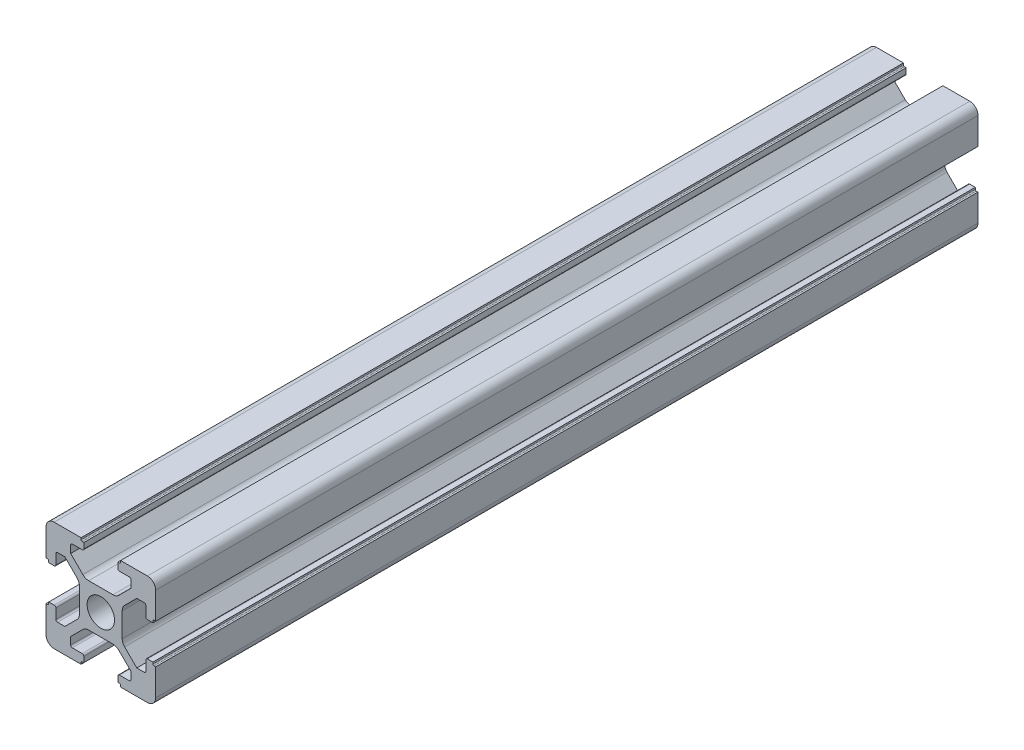
SolidWorks part; units mm, degrees
ref_plane "前视基准面" through (0, 0, 0) normal (0, 0, 1) x (1, 0, 0)
ref_plane "上视基准面" through (0, 0, 0) normal (0, 1, 0) x (1, 0, 0)
ref_plane "右视基准面" through (0, 0, 0) normal (1, 0, 0) x (0, 0, -1)
sketch "草图1" plane through (0, 0, 0) normal (0, 0, 1) x (1, 0, 0)
  line L0 (4.216, 3.2442) -> (6.4367, 5.4649)
  line L1 (6.4367, 5.4649) -> (7.7767, 5.4649)
  line L2 (8.0767, 5.1649) -> (8.0767, 3.3649)
  line L3 (8.3767, 3.0649) -> (9.3767, 3.0649)
  line L4 (9.3767, 3.0649) -> (9.3767, 3.3649)
  line L5 (9.5767, 3.5649) -> (9.8767, 3.5649)
  line L6 (9.8767, 3.5649) -> (9.8767, 8.4649)
  line L7 (8.3767, 9.9649) -> (3.4767, 9.9649)
  line L8 (3.4767, 9.9649) -> (3.4767, 9.6649)
  line L9 (3.2767, 9.4649) -> (2.9767, 9.4649)
  line L10 (2.9767, 9.4649) -> (2.9767, 8.4649)
  line L11 (3.2767, 8.1649) -> (5.0767, 8.1649)
  line L12 (5.3767, 7.8649) -> (5.3767, 6.5249)
  line L13 (5.3767, 6.5249) -> (3.156, 4.3042)
  line L14 (2.0953, 3.8649) -> (-2.342, 3.8649)
  line L15 (-3.4027, 4.3042) -> (-5.6233, 6.5249)
  line L16 (-5.6233, 6.5249) -> (-5.6233, 7.8649)
  line L17 (-5.3233, 8.1649) -> (-3.5233, 8.1649)
  line L18 (-3.2233, 8.4649) -> (-3.2233, 9.4649)
  line L19 (-3.2233, 9.4649) -> (-3.5233, 9.4649)
  line L20 (-3.7233, 9.6649) -> (-3.7233, 9.9649)
  line L21 (-3.7233, 9.9649) -> (-8.6233, 9.9649)
  line L22 (-10.1233, 8.4649) -> (-10.1233, 3.5649)
  line L23 (-10.1233, 3.5649) -> (-9.8233, 3.5649)
  line L24 (-9.6233, 3.3649) -> (-9.6233, 3.0649)
  line L25 (-9.6233, 3.0649) -> (-8.6233, 3.0649)
  line L26 (-8.3233, 3.3649) -> (-8.3233, 5.1649)
  line L27 (-8.0233, 5.4649) -> (-6.6833, 5.4649)
  line L28 (-6.6833, 5.4649) -> (-4.4627, 3.2442)
  line L29 (-4.0233, 2.1836) -> (-4.0233, -2.2538)
  line L30 (-4.4627, -3.3144) -> (-6.6833, -5.5351)
  line L31 (-6.6833, -5.5351) -> (-8.0233, -5.5351)
  line L32 (-8.3233, -5.2351) -> (-8.3233, -3.4351)
  line L33 (-8.6233, -3.1351) -> (-9.6233, -3.1351)
  line L34 (-9.6233, -3.1351) -> (-9.6233, -3.4351)
  line L35 (-9.8233, -3.6351) -> (-10.1233, -3.6351)
  line L36 (-10.1233, -3.6351) -> (-10.1233, -8.5351)
  line L37 (-8.6233, -10.0351) -> (-3.7233, -10.0351)
  line L38 (-3.7233, -10.0351) -> (-3.7233, -9.7351)
  line L39 (-3.5233, -9.5351) -> (-3.2233, -9.5351)
  line L40 (-3.2233, -9.5351) -> (-3.2233, -8.5351)
  line L41 (-3.5233, -8.2351) -> (-5.3233, -8.2351)
  line L42 (-5.6233, -7.9351) -> (-5.6233, -6.5951)
  line L43 (-5.6233, -6.5951) -> (-3.4027, -4.3744)
  line L44 (-2.342, -3.9351) -> (2.0953, -3.9351)
  line L45 (3.156, -4.3744) -> (5.3767, -6.5951)
  line L46 (5.3767, -6.5951) -> (5.3767, -7.9351)
  line L47 (5.0767, -8.2351) -> (3.2767, -8.2351)
  line L48 (2.9767, -8.5351) -> (2.9767, -9.5351)
  line L49 (2.9767, -9.5351) -> (3.2767, -9.5351)
  line L50 (3.4767, -9.7351) -> (3.4767, -10.0351)
  line L51 (3.4767, -10.0351) -> (8.3767, -10.0351)
  line L52 (9.8767, -8.5351) -> (9.8767, -3.6351)
  line L53 (9.8767, -3.6351) -> (9.5767, -3.6351)
  line L54 (9.3767, -3.4351) -> (9.3767, -3.1351)
  line L55 (9.3767, -3.1351) -> (8.3767, -3.1351)
  line L56 (8.0767, -3.4351) -> (8.0767, -5.2351)
  line L57 (7.7767, -5.5351) -> (6.4367, -5.5351)
  line L58 (6.4367, -5.5351) -> (4.216, -3.3144)
  line L59 (3.7767, -2.2538) -> (3.7767, 2.1836)
  circle A0 centre (-0.1233, -0.0351) radius 2.5
  arc A1 (8.0767, 5.1649) -> (7.7767, 5.4649) centre (7.7767, 5.1649) ccw
  arc A2 (8.0767, 3.3649) -> (8.3767, 3.0649) centre (8.3767, 3.3649) ccw
  arc A3 (9.5767, 3.5649) -> (9.3767, 3.3649) centre (9.5767, 3.3649) ccw
  arc A4 (9.8767, 8.4649) -> (8.3767, 9.9649) centre (8.3767, 8.4649) ccw
  arc A5 (3.2767, 9.4649) -> (3.4767, 9.6649) centre (3.2767, 9.6649) ccw
  arc A6 (2.9767, 8.4649) -> (3.2767, 8.1649) centre (3.2767, 8.4649) ccw
  arc A7 (5.3767, 7.8649) -> (5.0767, 8.1649) centre (5.0767, 7.8649) ccw
  arc A8 (2.0953, 3.8649) -> (3.156, 4.3042) centre (2.0953, 5.3649) ccw
  arc A9 (-3.4027, 4.3042) -> (-2.342, 3.8649) centre (-2.342, 5.3649) ccw
  arc A10 (-5.3233, 8.1649) -> (-5.6233, 7.8649) centre (-5.3233, 7.8649) ccw
  arc A11 (-3.5233, 8.1649) -> (-3.2233, 8.4649) centre (-3.5233, 8.4649) ccw
  arc A12 (-3.7233, 9.6649) -> (-3.5233, 9.4649) centre (-3.5233, 9.6649) ccw
  arc A13 (-8.6233, 9.9649) -> (-10.1233, 8.4649) centre (-8.6233, 8.4649) ccw
  arc A14 (-9.6233, 3.3649) -> (-9.8233, 3.5649) centre (-9.8233, 3.3649) ccw
  arc A15 (-8.6233, 3.0649) -> (-8.3233, 3.3649) centre (-8.6233, 3.3649) ccw
  arc A16 (-8.0233, 5.4649) -> (-8.3233, 5.1649) centre (-8.0233, 5.1649) ccw
  arc A17 (-4.0233, 2.1836) -> (-4.4627, 3.2442) centre (-5.5233, 2.1836) ccw
  arc A18 (-4.4627, -3.3144) -> (-4.0233, -2.2538) centre (-5.5233, -2.2538) ccw
  arc A19 (-8.3233, -5.2351) -> (-8.0233, -5.5351) centre (-8.0233, -5.2351) ccw
  arc A20 (-8.3233, -3.4351) -> (-8.6233, -3.1351) centre (-8.6233, -3.4351) ccw
  arc A21 (-9.8233, -3.6351) -> (-9.6233, -3.4351) centre (-9.8233, -3.4351) ccw
  arc A22 (-10.1233, -8.5351) -> (-8.6233, -10.0351) centre (-8.6233, -8.5351) ccw
  arc A23 (-3.5233, -9.5351) -> (-3.7233, -9.7351) centre (-3.5233, -9.7351) ccw
  arc A24 (-3.2233, -8.5351) -> (-3.5233, -8.2351) centre (-3.5233, -8.5351) ccw
  arc A25 (-5.6233, -7.9351) -> (-5.3233, -8.2351) centre (-5.3233, -7.9351) ccw
  arc A26 (-2.342, -3.9351) -> (-3.4027, -4.3744) centre (-2.342, -5.4351) ccw
  arc A27 (3.156, -4.3744) -> (2.0953, -3.9351) centre (2.0953, -5.4351) ccw
  arc A28 (5.0767, -8.2351) -> (5.3767, -7.9351) centre (5.0767, -7.9351) ccw
  arc A29 (3.2767, -8.2351) -> (2.9767, -8.5351) centre (3.2767, -8.5351) ccw
  arc A30 (3.4767, -9.7351) -> (3.2767, -9.5351) centre (3.2767, -9.7351) ccw
  arc A31 (8.3767, -10.0351) -> (9.8767, -8.5351) centre (8.3767, -8.5351) ccw
  arc A32 (9.3767, -3.4351) -> (9.5767, -3.6351) centre (9.5767, -3.4351) ccw
  arc A33 (8.3767, -3.1351) -> (8.0767, -3.4351) centre (8.3767, -3.4351) ccw
  arc A34 (7.7767, -5.5351) -> (8.0767, -5.2351) centre (7.7767, -5.2351) ccw
  arc A35 (3.7767, -2.2538) -> (4.216, -3.3144) centre (5.2767, -2.2538) ccw
  arc A36 (4.216, 3.2442) -> (3.7767, 2.1836) centre (5.2767, 2.1836) ccw
extrude "凸台-拉伸1" add sketch "草图1" along normal blind 150
